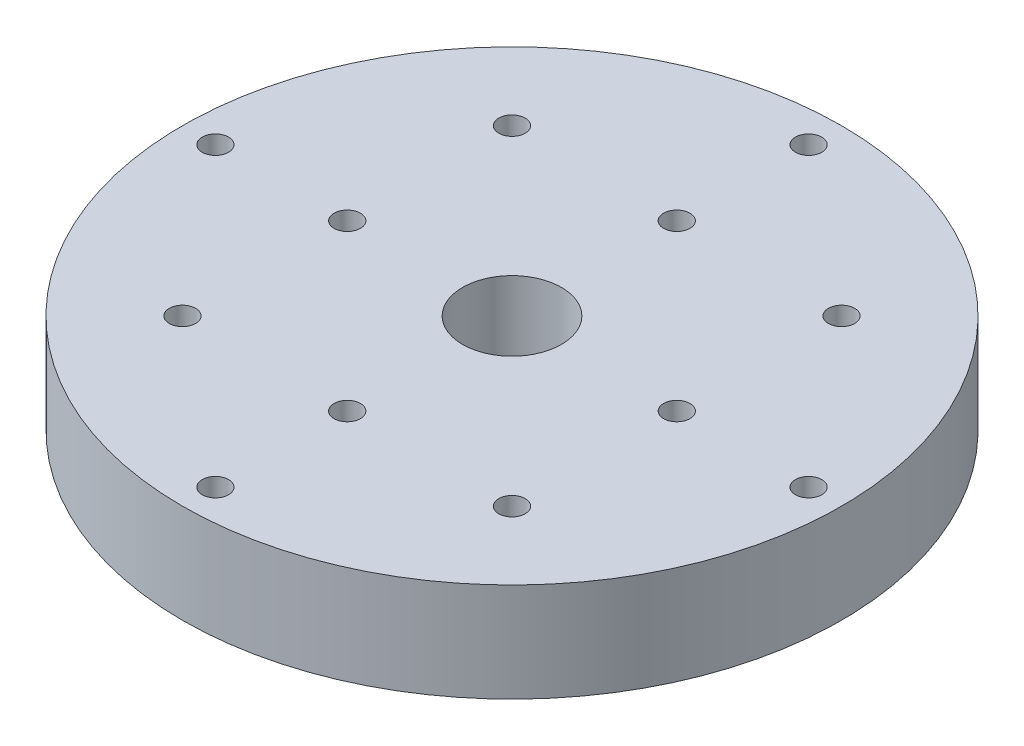
SolidWorks part; units mm, degrees
ref_plane "Front Plane" through (0, 0, 0) normal (0, 0, 1) x (1, 0, 0)
ref_plane "Top Plane" through (0, 0, 0) normal (0, 1, 0) x (1, 0, 0)
ref_plane "Right Plane" through (0, 0, 0) normal (1, 0, 0) x (0, 0, -1)
sketch "Sketch1" plane through (0, 0, 0) normal (0, 1, 0) x (1, 0, 0)
  circle A0 centre (0, 0) radius 50
  dimension "D1" = 100
extrude "Boss-Extrude1" add sketch "Sketch1" along normal blind 15
sketch "Sketch2" plane through (0, 15, 0) normal (0, 1, 0) x (1, 0, 0)
  line L0 (0, 25) -> (0, -25) construction
  line L1 (25, 0) -> (-25, 0) construction
  line L2 (-45, 0) -> (45, 0) construction
  line L3 (-25, -25) -> (25, -25) construction
  line L4 (-25, -25) -> (-25, 25) construction
  line L5 (-25, 25) -> (25, 25) construction
  line L6 (25, -25) -> (25, 25) construction
  line L7 (-25, -25) -> (25, 25) construction
  line L8 (-25, 25) -> (25, -25) construction
  line L9 (0, 45) -> (0, -45) construction
  circle A0 centre (0, 0) radius 7.5
  circle A2 centre (45, 0) radius 2
  circle A3 centre (0, -45) radius 2
  circle A4 centre (0, -25) radius 2
  circle A5 centre (25, -25) radius 2
  circle A6 centre (-25, -25) radius 2
  circle A7 centre (-25, 0) radius 2
  circle A8 centre (-45, 0) radius 2
  circle A9 centre (-25, 25) radius 2
  circle A10 centre (0, 45) radius 2
  circle A11 centre (0, 25) radius 2
  circle A12 centre (25, 25) radius 2
  circle A13 centre (25, 0) radius 2
  point P16 (0, 0)
  point P17 (0, 0)
  dimension "D1" = 15
  dimension "D6" = 4
  dimension "D2" = 50
  dimension "D3" = 50
  dimension "D4" = 90
  dimension "D5" = 90
extrude "Cut-Extrude1" cut sketch "Sketch2" against normal through all
